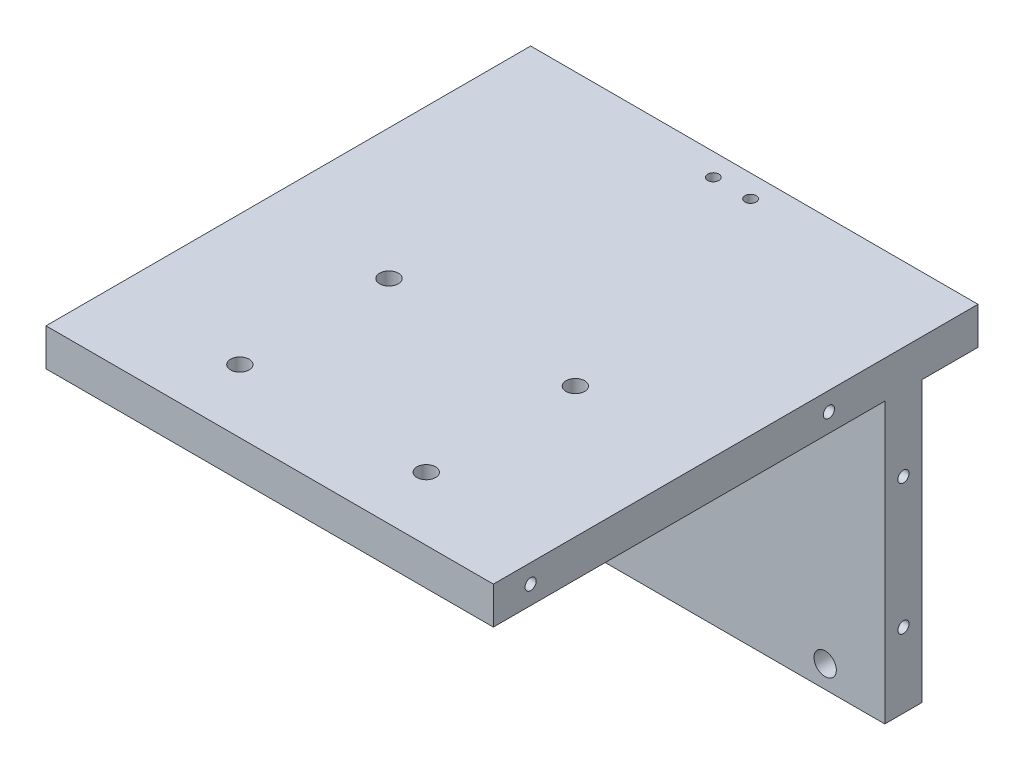
SolidWorks part; units mm, degrees
ref_plane "Front Plane" through (0, 0, 0) normal (0, 0, 1) x (1, 0, 0)
ref_plane "Top Plane" through (0, 0, 0) normal (0, 1, 0) x (1, 0, 0)
ref_plane "Right Plane" through (0, 0, 0) normal (1, 0, 0) x (0, 0, -1)
sketch "Sketch1" plane through (0, 0, 0) normal (0, 0, 1) x (1, 0, 0)
  line L1 (-60, 37.5) -> (60, 37.5)
  line L2 (-60, 37.5) -> (-60, -37.5)
  line L3 (-60, -37.5) -> (60, -37.5)
  line L4 (60, 37.5) -> (60, -37.5)
  line L5 (-60, 37.5) -> (60, -37.5) construction
  line L6 (-60, -37.5) -> (60, 37.5) construction
  circle A0 centre (-44, 31.5) radius 3
  circle A1 centre (44, 31.5) radius 3
  circle A2 centre (-44, -31.5) radius 3
  circle A3 centre (44, -31.5) radius 3
  point P0 (0, 0)
  dimension "D3" = 6
  dimension "D1" = 120
  dimension "D2" = 75
  dimension "D4" = 16
  dimension "D5" = 6
  dimension "D6" = 2
  dimension "D7" = 2
extrude "Boss-Extrude1" add sketch "Sketch1" along normal blind 10
sketch "Sketch2" plane through (0, 0, 10) normal (0, 0, 1) x (1, 0, 0)
  circle A0 centre (0, 10) radius 2.5
  circle A1 centre (0, -10) radius 2.5
  dimension "D1" = 5
  dimension "D2" = 10
  dimension "D3" = 2
extrude "Cut-Extrude1" cut sketch "Sketch2" against normal up to surface (10 mm away) up to face at (-41, -31.5, 0)
sketch "Sketch3" plane through (60, 0, 0) normal (1, 0, 0) x (0, 0, -1)
  line L0 (-10, 37.5) -> (0, 37.5) construction
  line L1 (0, -37.5) -> (0, 37.5) construction
  circle A0 centre (-5, 17.5) radius 1.5
  circle A1 centre (-5, -17.5) radius 1.5
  dimension "D1" = 3
  dimension "D2" = 20
  dimension "D4" = 35
  dimension "D5" = 5
  dimension "D3" = 2
extrude "Cut-Extrude2" cut sketch "Sketch3" against normal blind 10
pattern_linear "LPattern1" count 2 spacing 110 along (-1, 0, 0) of "Cut-Extrude2"
sketch "Sketch4" plane through (0, 37.5, 0) normal (0, 1, 0) x (1, 0, 0)
  line L0 (60, 0) -> (-60, 0) construction
  line L1 (-60, 15) -> (60, 15)
  line L2 (-60, 15) -> (-60, -115)
  line L3 (-60, -115) -> (60, -115)
  line L4 (60, 15) -> (60, -115)
  line L5 (60, -10) -> (60, 0) construction
  line L6 (-60, -10) -> (-60, 0) construction
  dimension "D1" = 130
  dimension "D2" = 15
extrude "Boss-Extrude2" add sketch "Sketch4" along normal blind 10
sketch "Sketch5" plane through (60, 0, 0) normal (1, 0, 0) x (0, 0, -1)
  line L0 (-115, 37.5) -> (-10, 37.5) construction
  line L1 (-115, 47.5) -> (-115, 37.5) construction
  circle A0 centre (-105, 42.5) radius 1.5
  circle A1 centre (-25, 42.5) radius 1.5
  dimension "D1" = 3
  dimension "D2" = 5
  dimension "D3" = 10
  dimension "D5" = 80
  dimension "D4" = 2
extrude "Cut-Extrude3" cut sketch "Sketch5" against normal blind 10
pattern_linear "LPattern2" count 2 spacing 110 along (-1, 0, 0) of "Cut-Extrude3"
sketch "Sketch6" plane through (0, 47.5, 0) normal (0, 1, 0) x (1, 0, 0)
  line L0 (-60, -115) -> (60, -115) construction
  line L1 (-60, 15) -> (-60, -115) construction
  line L2 (60, -115) -> (60, 15) construction
  circle A0 centre (-25, -98) radius 2.5
  circle A1 centre (25, -98) radius 2.5
  circle A2 centre (-25, -58) radius 2.5
  circle A3 centre (25, -58) radius 2.5
  dimension "D1" = 5
  dimension "D2" = 17
  dimension "D3" = 35
  dimension "D5" = 35
  dimension "D4" = 2
  dimension "D6" = 2
extrude "Cut-Extrude4" cut sketch "Sketch6" against normal blind 10
sketch "Sketch7" plane through (0, 47.5, 0) normal (0, 1, 0) x (1, 0, 0)
  line L0 (-60, 15) -> (-60, -115) construction
  line L1 (60, 15) -> (-60, 15) construction
  circle A0 centre (-5, 9) radius 1.5
  circle A1 centre (5, 9) radius 1.5
  dimension "D1" = 3
  dimension "D4" = 2
  dimension "D2" = 55
  dimension "D3" = 6
extrude "Cut-Extrude5" cut sketch "Sketch7" against normal blind 10
